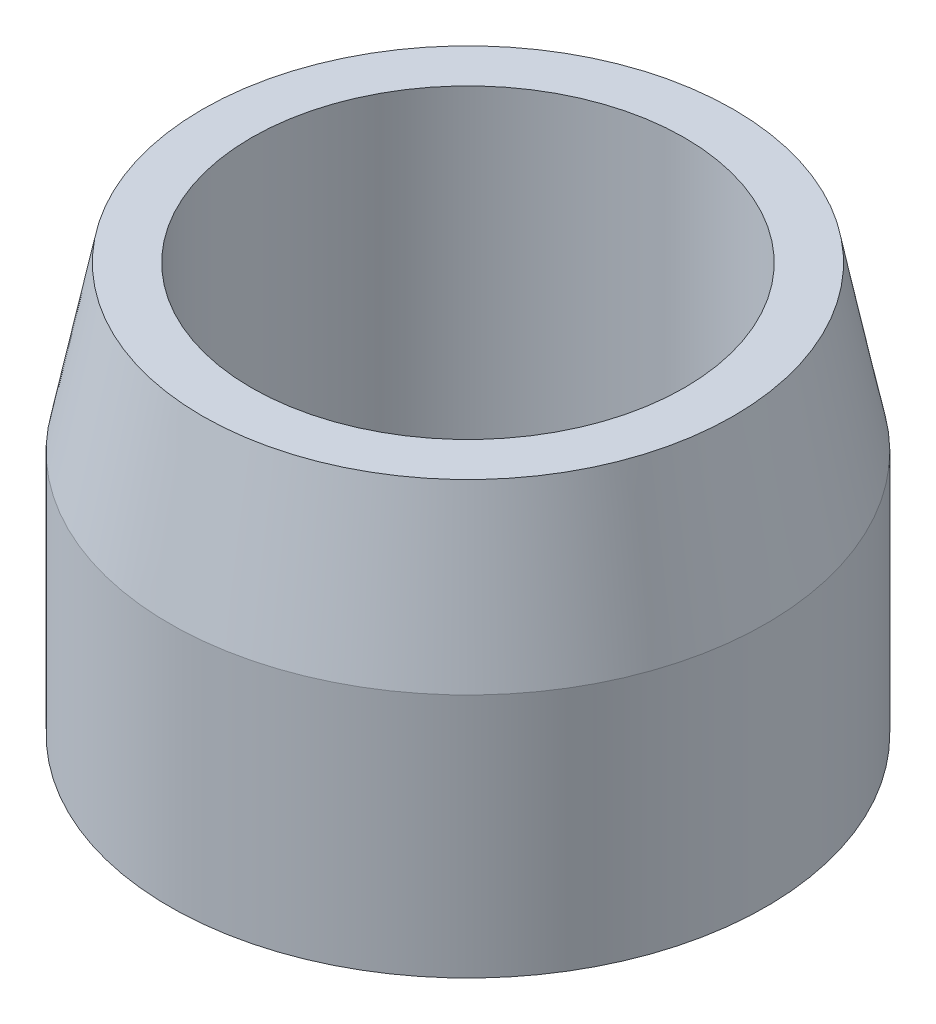
SolidWorks part; units mm, degrees
ref_plane "前视基准面" through (0, 0, 0) normal (0, 0, 1) x (1, 0, 0)
ref_plane "上视基准面" through (0, 0, 0) normal (0, 1, 0) x (1, 0, 0)
ref_plane "右视基准面" through (0, 0, 0) normal (1, 0, 0) x (0, 0, -1)
other "Configuration Table"
sketch "草图1" plane through (0, 0, 0) normal (0, 0, 1) x (1, 0, 0)
  line L0 (0, 0) -> (0, 5) construction
  line L1 (0, 0) -> (2.65, 0) construction
  line L2 (2.65, 0) -> (2.65, 5)
  line L3 (2.65, 0) -> (3.65, 0)
  line L4 (3.65, 0) -> (3.65, 3)
  line L5 (3.65, 3) -> (3.25, 5)
  line L6 (2.65, 5) -> (3.25, 5)
  dimension "D1" = 5
  dimension "D2" = 2.65
  dimension "D3" = 1
  dimension "D4" = 3
  dimension "D5" = 0.6
revolve "旋转1" add sketch "草图1" angle 360 about L0
